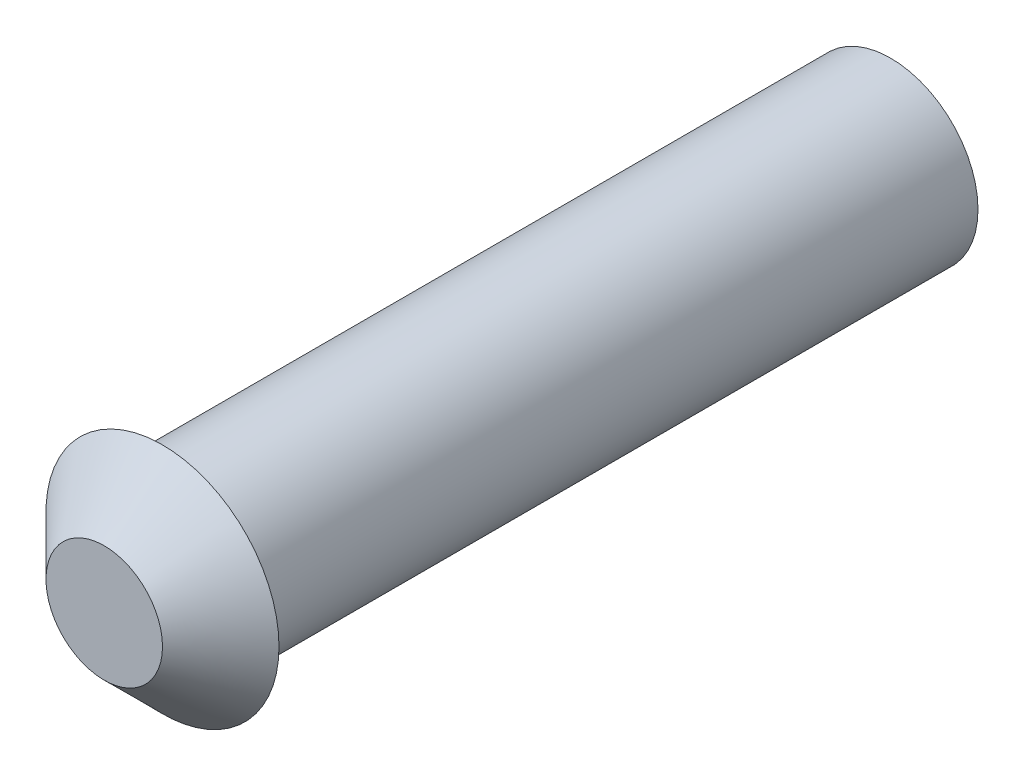
SolidWorks part; units mm, degrees
material "1060 Alloy"
ref_plane "Front Plane" through (0, 0, 0) normal (0, 0, 1) x (1, 0, 0)
ref_plane "Top Plane" through (0, 0, 0) normal (0, 1, 0) x (1, 0, 0)
ref_plane "Right Plane" through (0, 0, 0) normal (1, 0, 0) x (0, 0, -1)
sketch "Sketch1" plane through (0, 0, 0) normal (0, 0, 1) x (1, 0, 0)
  circle A0 centre (0, 0) radius 1.905
  dimension "D1" = 3.81
extrude "Boss-Extrude1" add sketch "Sketch1" along normal mid plane 15.875
sketch "Sketch2" plane through (0, 0, 7.9375) normal (0, 0, 1) x (1, 0, 0)
  circle A0 centre (0, 0) radius 2.54
  dimension "D1" = 5.08
ref_plane "Plane1" through (0, 0, 9.2075) normal (0, 0, 1) x (1, 0, 0)
sketch "Sketch3" plane through (0, 0, 9.2075) normal (0, 0, 1) x (1, 0, 0)
  circle A0 centre (0, 0) radius 1.27
  dimension "D1" = 2.54
loft "Loft2" add profiles "Sketch2", "Sketch3"
